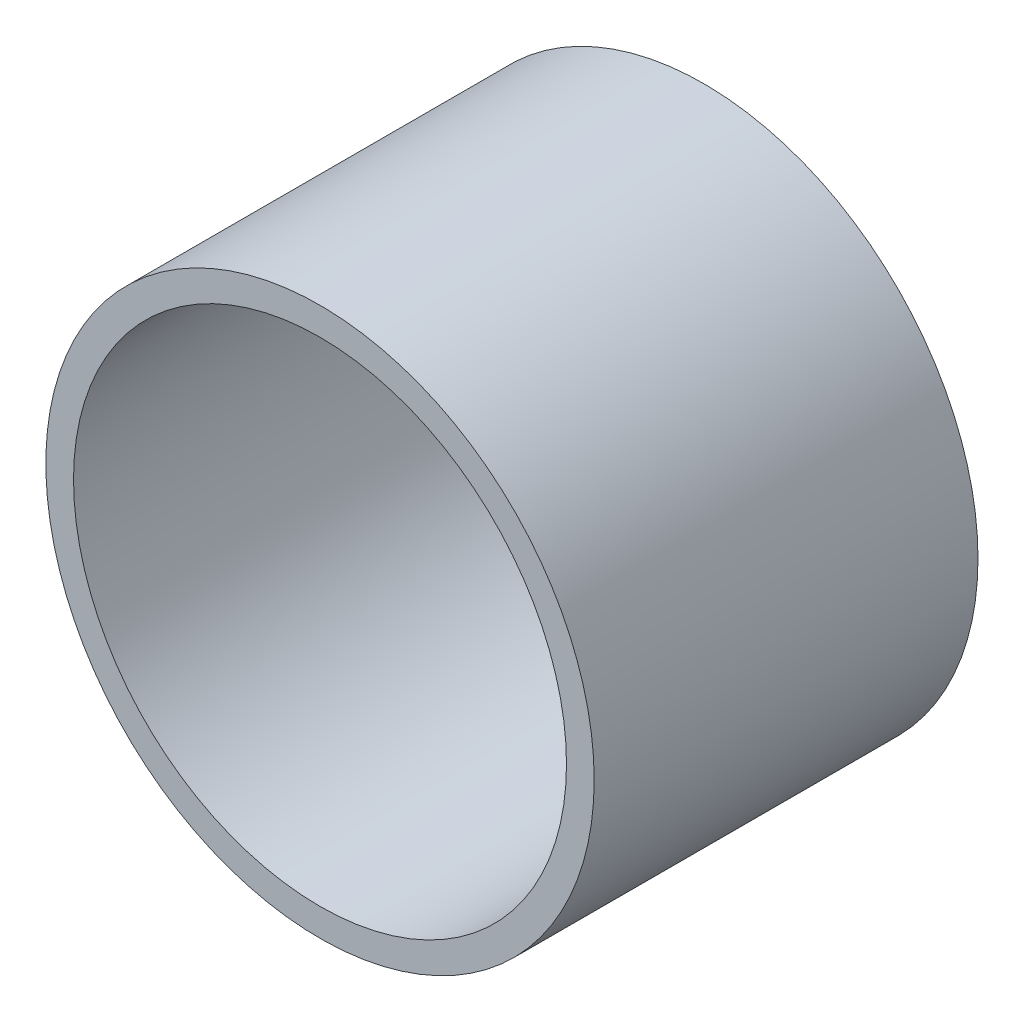
SolidWorks part; units mm, degrees
ref_plane "Front Plane" through (0, 0, 0) normal (0, 0, 1) x (1, 0, 0)
ref_plane "Top Plane" through (0, 0, 0) normal (0, 1, 0) x (1, 0, 0)
ref_plane "Right Plane" through (0, 0, 0) normal (1, 0, 0) x (0, 0, -1)
sketch "Sketch1" plane through (0, 0, 0) normal (0, 0, 1) x (1, 0, 0)
  circle A0 centre (0, 0) radius 25.146
  circle A1 centre (0, 0) radius 22.606
  dimension "D1" = 2.54
  dimension "D2" = 45.212
extrude "Boss-Extrude1" add sketch "Sketch1" along normal blind 35.2
